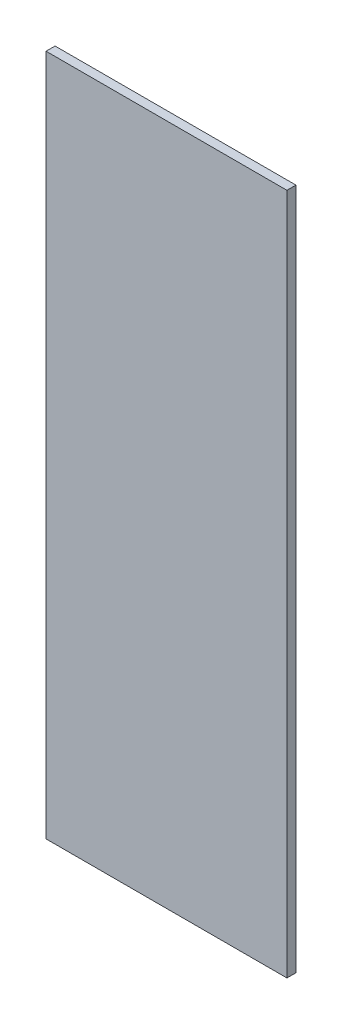
SolidWorks part; units mm, degrees
ref_plane "Plan de face" through (0, 0, 0) normal (0, 0, 1) x (1, 0, 0)
ref_plane "Plan de dessus" through (0, 0, 0) normal (0, 1, 0) x (1, 0, 0)
ref_plane "Plan de droite" through (0, 0, 0) normal (1, 0, 0) x (0, 0, -1)
sketch "Esquisse1" plane through (0, 0, 0) normal (0, 0, 1) x (1, 0, 0)
  line L1 (-53.5, -151.5) -> (53.5, -151.5)
  line L2 (-53.5, -151.5) -> (-53.5, 151.5)
  line L3 (-53.5, 151.5) -> (53.5, 151.5)
  line L4 (53.5, -151.5) -> (53.5, 151.5)
  line L5 (-53.5, -151.5) -> (53.5, 151.5) construction
  line L6 (-53.5, 151.5) -> (53.5, -151.5) construction
  point P0 (0, 0)
  dimension "D1" = 107
  dimension "D2" = 303
extrude "Boss.-Extru.1" add sketch "Esquisse1" along normal blind 4
